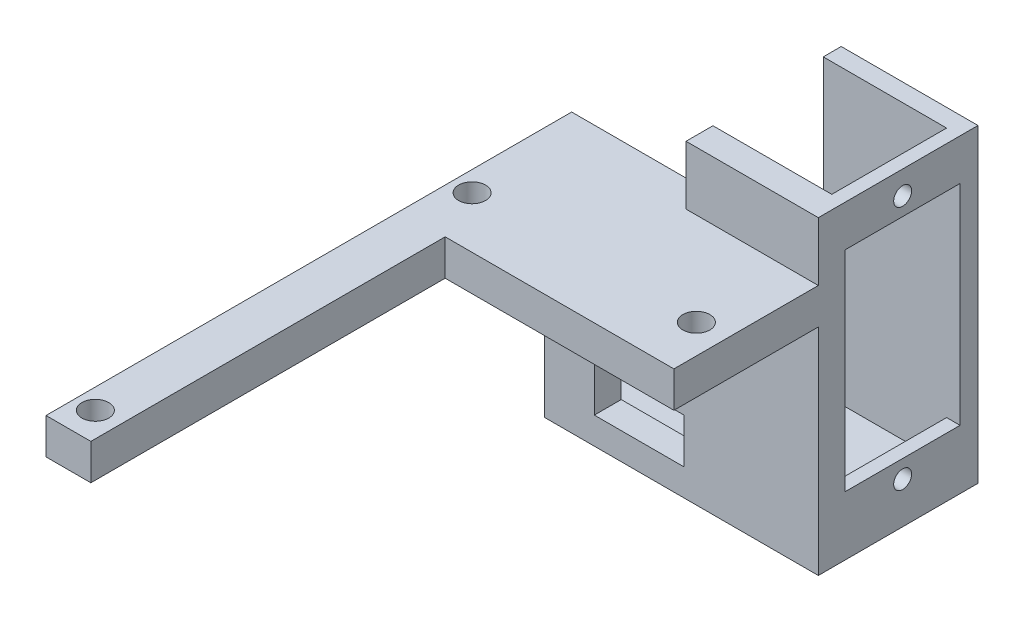
SolidWorks part; units mm, degrees
ref_plane "Front Plane" through (0, 0, 0) normal (0, 0, 1) x (1, 0, 0)
ref_plane "Top Plane" through (0, 0, 0) normal (0, 1, 0) x (1, 0, 0)
ref_plane "Right Plane" through (0, 0, 0) normal (1, 0, 0) x (0, 0, -1)
sketch "Sketch1" plane through (0, 0, 0) normal (0, 1, 0) x (1, 0, 0)
  line L1 (-41.2344, 20.8984) -> (-36.2344, 20.8984)
  line L2 (-41.2344, 20.8984) -> (-41.2344, -32.6016)
  line L3 (-41.2344, -32.6016) -> (-36.2344, -32.6016)
  line L4 (-36.2344, 20.8984) -> (-36.2344, -32.6016)
  line L5 (-36.2344, 20.8984) -> (-10.7344, 20.8984)
  line L6 (-36.2344, 20.8984) -> (-36.2344, 6.8984)
  line L7 (-36.2344, 6.8984) -> (-10.7344, 6.8984)
  line L8 (-10.7344, 20.8984) -> (-10.7344, 6.8984)
  dimension "D1" = 53.5
  dimension "D2" = 5
  dimension "D3" = 25.5
  dimension "D4" = 14
extrude "Boss-Extrude1" add sketch "Sketch1" along normal blind 4 contours L8 L5 L4 L7
sketch "Sketch2" plane through (0, 4, 0) normal (0, 1, 0) x (1, 0, 0)
  line L2 (-41.2344, 20.8984) -> (-10.7344, 20.8984) construction
  circle A0 centre (-38.9844, -29.3516) radius 1.5
  circle A1 centre (-38.9844, 12.6484) radius 1.5
  circle A2 centre (-13.9844, 12.6484) radius 1.5
  dimension "D1" = 3
  dimension "D2" = 50.25
  dimension "D3" = 3
  dimension "D4" = 8.25
  dimension "D6" = 8.25
  dimension "D7" = 3
  dimension "D8" = 25
extrude "Cut-Extrude1" cut sketch "Sketch2" against normal through all
sketch "Sketch3" plane through (0, 0, -20.8984) normal (0, 0, -1) x (-1, 0, 0)
  line L4 (10.7344, 0) -> (41.2344, 0)
  line L5 (41.2344, 0) -> (41.2344, 4)
  line L6 (41.2344, 4) -> (10.7344, 4)
  line L7 (10.7344, 4) -> (10.7344, 0)
  line L8 (10.7344, 0) -> (41.2344, 0)
  line L9 (41.2344, 0) -> (41.2344, 4)
  line L10 (41.2344, 4) -> (10.7344, 4)
  line L11 (10.7344, 4) -> (10.7344, 0)
  dimension "D1" = 0
extrude "Boss-Extrude2" add sketch "Sketch3" along normal blind 5.1
sketch "Sketch4" plane through (0, 0, 0) normal (0, -1, 0) x (1, 0, 0)
  line L0 (-41.2344, -25.9984) -> (-41.2344, 32.6016) construction
  line L1 (-10.7344, -25.9984) -> (-41.2344, -25.9984)
  line L2 (-10.7344, -25.9984) -> (-10.7344, -22.9984)
  line L3 (-10.7344, -22.9984) -> (-41.2344, -22.9984)
  line L4 (-41.2344, -25.9984) -> (-41.2344, -22.9984)
  dimension "D1" = 3
extrude "Boss-Extrude3" add sketch "Sketch4" along normal blind 24
sketch "Sketch5" plane through (0, 0, -25.9984) normal (0, 0, -1) x (-1, 0, 0)
  line L0 (10.7344, 4) -> (10.7344, -24) construction
  line L1 (10.7344, -22) -> (41.2344, -22)
  line L2 (10.7344, -22) -> (10.7344, -24)
  line L3 (10.7344, -24) -> (41.2344, -24)
  line L4 (41.2344, -22) -> (41.2344, -24)
  dimension "D1" = 2
extrude "Boss-Extrude8" add sketch "Sketch5" along normal blind 14.8 contours L1 L4 L3 L2
sketch "Sketch10" plane through (0, -22, 0) normal (0, 1, 0) x (1, 0, 0)
  line L0 (-10.7344, 40.7984) -> (-10.7344, 25.9984) construction
  line L1 (-41.2344, 40.7984) -> (-10.7344, 40.7984)
  line L2 (-41.2344, 40.7984) -> (-41.2344, 38.7984)
  line L3 (-41.2344, 38.7984) -> (-10.7344, 38.7984)
  line L4 (-10.7344, 40.7984) -> (-10.7344, 38.7984)
  dimension "D1" = 2
extrude "Boss-Extrude9" add sketch "Sketch10" along normal blind 16.8
sketch "Sketch11" plane through (0, -22, 0) normal (0, 1, 0) x (1, 0, 0)
  line L0 (-41.2344, 38.7984) -> (-10.7344, 38.7984) construction
  line L1 (-10.7344, 25.9984) -> (-12.2344, 25.9984)
  line L2 (-10.7344, 25.9984) -> (-10.7344, 38.7984)
  line L3 (-10.7344, 38.7984) -> (-12.2344, 38.7984)
  line L4 (-12.2344, 25.9984) -> (-12.2344, 38.7984)
  dimension "D1" = 1.5
extrude "Boss-Extrude10" add sketch "Sketch11" along normal blind 4.6
sketch "Sketch13" plane through (0, -5.2, 0) normal (0, 1, 0) x (1, 0, 0)
  line L0 (-41.2344, 38.7984) -> (-10.7344, 38.7984) construction
  line L1 (-10.7344, 40.7984) -> (-25.9844, 40.7984)
  line L2 (-10.7344, 40.7984) -> (-10.7344, 38.7984)
  line L3 (-10.7344, 38.7984) -> (-25.9844, 38.7984)
  line L4 (-25.9844, 40.7984) -> (-25.9844, 38.7984)
extrude "Boss-Extrude11" add sketch "Sketch13" along normal blind 15.75
ref_plane "Plane1" through (0, -5.725, 0) normal (0, -1, 0) x (-1, 0, 0)
sketch "Sketch14" plane through (0, 0, -22.9984) normal (0, 0, 1) x (1, 0, 0)
  line L0 (-10.7344, -24) -> (-41.2344, -24) construction
  line L1 (-35.7068, -16) -> (-25.7068, -16)
  line L2 (-35.7068, -16) -> (-35.7068, -21)
  line L3 (-35.7068, -21) -> (-25.7068, -21)
  line L4 (-25.7068, -16) -> (-25.7068, -21)
  dimension "D1" = 5
  dimension "D2" = 10
  dimension "D3" = 3
extrude "Cut-Extrude5" cut sketch "Sketch14" against normal blind 3
sketch "Sketch15" plane through (0, 4, 0) normal (0, 1, 0) x (1, 0, 0)
  line L1 (-10.7344, 25.9984) -> (-25.4844, 25.9984)
  line L2 (-10.7344, 25.9984) -> (-10.7344, 22.9984)
  line L3 (-10.7344, 22.9984) -> (-25.4844, 22.9984)
  line L4 (-25.4844, 25.9984) -> (-25.4844, 22.9984)
  dimension "D1" = 3
  dimension "D2" = 14.75
sketch "Sketch16" plane through (-10.7344, 0, 0) normal (1, 0, 0) x (0, 0, -1)
  line L0 (25.9984, -17.4) -> (38.7984, -17.4) construction
  circle A0 centre (32.3984, -19.4) radius 1
  point P6 (32.3984, -17.4)
  dimension "D1" = 2
  dimension "D2" = 2
extrude "Cut-Extrude6" cut sketch "Sketch16" against normal blind 10
mirror "Mirror1" about plane through (0, -5.725, 0) normal (0, -1, 0) of "Boss-Extrude10", "Cut-Extrude6"
extrude "Boss-Extrude12" add sketch "Sketch15" along normal up to vertex (6.55 mm away) contours L3 L4 L1 L2
